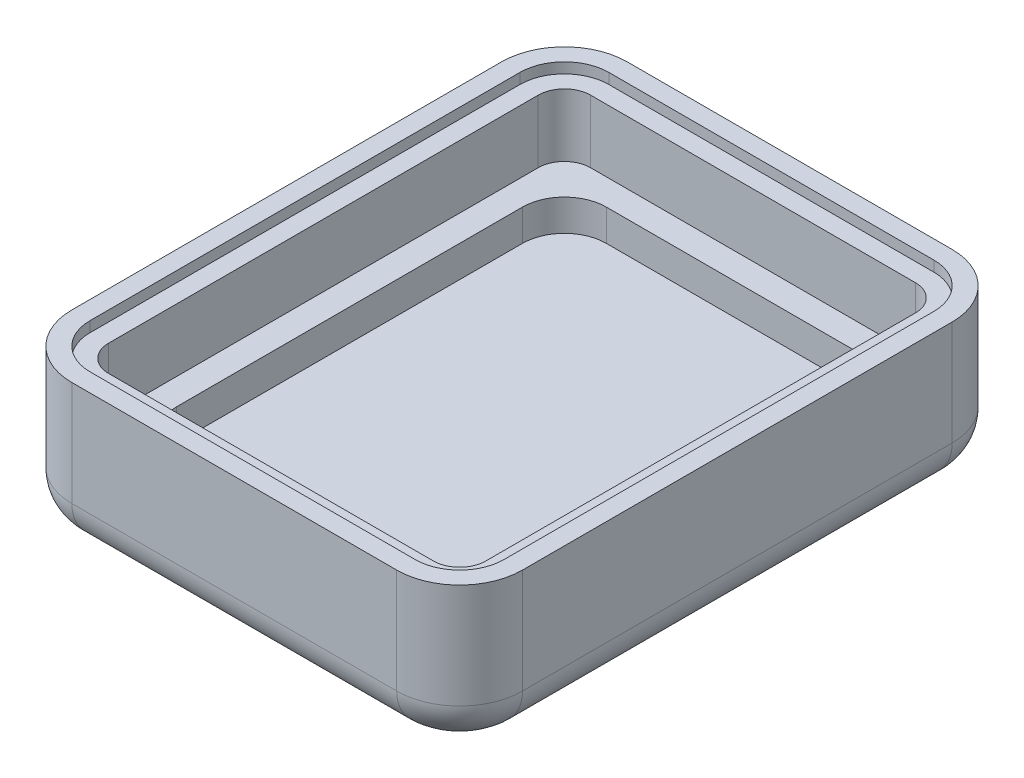
SolidWorks part; units mm, degrees
ref_plane "Front Plane" through (0, 0, 0) normal (0, 0, 1) x (1, 0, 0)
ref_plane "Top Plane" through (0, 0, 0) normal (0, 1, 0) x (1, 0, 0)
ref_plane "Right Plane" through (0, 0, 0) normal (1, 0, 0) x (0, 0, -1)
sketch "Sketch1" plane through (0, 0, 0) normal (0, 1, 0) x (1, 0, 0)
  line L1 (-7.75, -11.25) -> (7.75, -11.25) construction
  line L2 (-8.75, -10.25) -> (-8.75, 10.25) construction
  line L3 (-7.75, 11.25) -> (7.75, 11.25) construction
  line L4 (8.75, -10.25) -> (8.75, 10.25) construction
  line L5 (-8.75, -11.25) -> (8.75, 11.25) construction
  line L6 (-8.75, 11.25) -> (8.75, -11.25) construction
  line L7 (-7.75, -13.25) -> (7.75, -13.25)
  line L8 (-10.75, -10.25) -> (-10.75, 10.25)
  line L9 (-7.75, 13.25) -> (7.75, 13.25)
  line L10 (10.75, -10.25) -> (10.75, 10.25)
  line L11 (-10.75, -13.25) -> (10.75, 13.25) construction
  line L12 (-10.75, 13.25) -> (10.75, -13.25) construction
  arc A0 (-7.75, -11.25) -> (-8.75, -10.25) centre (-7.75, -10.25) cw construction
  arc A1 (7.75, -11.25) -> (8.75, -10.25) centre (7.75, -10.25) ccw construction
  arc A2 (7.75, 11.25) -> (8.75, 10.25) centre (7.75, 10.25) cw construction
  arc A3 (-8.75, 10.25) -> (-7.75, 11.25) centre (-7.75, 10.25) cw construction
  arc A4 (-10.75, 10.25) -> (-7.75, 13.25) centre (-7.75, 10.25) cw
  arc A5 (-7.75, -13.25) -> (-10.75, -10.25) centre (-7.75, -10.25) cw
  arc A6 (7.75, -13.25) -> (10.75, -10.25) centre (7.75, -10.25) ccw
  arc A7 (7.75, 13.25) -> (10.75, 10.25) centre (7.75, 10.25) cw
  point P0 (0, 0)
  point P18 (0, 0)
  dimension "D3" = 1
  dimension "D6" = 3
  dimension "D1" = 17.5
  dimension "D2" = 22.5
  dimension "D4" = 2
  dimension "D5" = 2
extrude "Boss-Extrude1" add sketch "Sketch1" along normal blind 2
sketch "Sketch2" plane through (0, 2, 0) normal (0, 1, 0) x (1, 0, 0)
  line L0 (7.75, 13.25) -> (-7.75, 13.25) construction
  line L1 (-7.75, -11.5) -> (7.75, -11.5)
  line L2 (-9, -10.25) -> (-9, 10.25)
  line L3 (-7.75, 11.5) -> (7.75, 11.5)
  line L4 (9, -10.25) -> (9, 10.25)
  line L5 (-9, -11.5) -> (9, 11.5) construction
  line L6 (-9, 11.5) -> (9, -11.5) construction
  line L7 (-7.75, -13.25) -> (7.75, -13.25)
  line L8 (-10.75, -10.25) -> (-10.75, 10.25)
  line L9 (-7.75, 13.25) -> (7.75, 13.25)
  line L10 (10.75, -10.25) -> (10.75, 10.25)
  line L11 (-10.75, -13.25) -> (10.75, 13.25) construction
  line L12 (-10.75, 13.25) -> (10.75, -13.25) construction
  line L13 (10.75, -10.25) -> (10.75, 10.25) construction
  arc A0 (-7.75, -11.5) -> (-9, -10.25) centre (-7.75, -10.25) cw
  arc A1 (7.75, -11.5) -> (9, -10.25) centre (7.75, -10.25) ccw
  arc A2 (7.75, 11.5) -> (9, 10.25) centre (7.75, 10.25) cw
  arc A3 (-9, 10.25) -> (-7.75, 11.5) centre (-7.75, 10.25) cw
  arc A4 (-7.75, -13.25) -> (-10.75, -10.25) centre (-7.75, -10.25) cw
  arc A5 (7.75, -13.25) -> (10.75, -10.25) centre (7.75, -10.25) ccw
  arc A6 (7.75, 13.25) -> (10.75, 10.25) centre (7.75, 10.25) cw
  arc A7 (-10.75, 10.25) -> (-7.75, 13.25) centre (-7.75, 10.25) cw
  point P0 (0, 0)
  point P18 (0, 0)
  dimension "D3" = 1.25
  dimension "D4" = 3
  dimension "D1" = 18
  dimension "D2" = 23
extrude "Boss-Extrude2" add sketch "Sketch2" along normal blind 5
sketch "Sketch3" plane through (0, 2, 0) normal (0, 1, 0) x (1, 0, 0)
  line L0 (9, -10.25) -> (-5.75, -10.25)
  line L1 (-7.75, -8.25) -> (-7.75, 8.25)
  line L2 (-5.75, 10.25) -> (9, 10.25)
  line L3 (9, 10.25) -> (9, 12.25)
  line L4 (9, 12.25) -> (-9.75, 12.25)
  line L5 (-9.75, 12.25) -> (-9.75, -12.25)
  line L6 (-9.75, -12.25) -> (9, -12.25)
  line L7 (9, -12.25) -> (9, -10.25)
  arc A0 (-5.75, -10.25) -> (-7.75, -8.25) centre (-5.75, -8.25) cw
  arc A1 (-7.75, 8.25) -> (-5.75, 10.25) centre (-5.75, 8.25) cw
  point P14 (-7.75, -10.25)
  dimension "D4" = 2
  dimension "D1" = 2
  dimension "D2" = 2
  dimension "D3" = 2
extrude "Boss-Extrude3" add sketch "Sketch3" along normal blind 1.5
fillet "Fillet1" radius 2 8 edges at (10.75, 0, 0) (9.8713, 0, 12.3713) (0, 0, 13.25) (-9.8713, 0, 12.3713) (-10.75, 0, 0) (-9.8713, 0, -12.3713) (0, 0, -13.25) (9.8713, 0, -12.3713)
sketch "Sketch4" plane through (0, 7, 0) normal (0, 1, 0) x (1, 0, 0)
  line L0 (7.75, 11.5) -> (-7.75, 11.5) construction
  line L3 (-7.75, 12.375) -> (7.75, 12.375)
  line L4 (9.875, 10.25) -> (9.875, -10.25)
  line L5 (7.75, -12.375) -> (-7.75, -12.375)
  line L6 (-9.875, -10.25) -> (-9.875, 10.25)
  line L7 (-10.75, 10.25) -> (-10.75, -10.25) construction
  line L8 (10.75, -10.25) -> (10.75, 10.25) construction
  line L9 (-7.75, -13.25) -> (7.75, -13.25) construction
  arc A1 (9.875, -10.25) -> (7.75, -12.375) centre (7.75, -10.25) cw
  arc A2 (-7.75, -12.375) -> (-9.875, -10.25) centre (-7.75, -10.25) cw
  arc A3 (-9.875, 10.25) -> (-7.75, 12.375) centre (-7.75, 10.25) cw
  arc A4 (7.75, 12.375) -> (9.875, 10.25) centre (7.75, 10.25) cw
  dimension "D5" = 2.125
  dimension "D1" = 0.875
  dimension "D2" = 0.875
  dimension "D3" = 0.875
  dimension "D4" = 0.875
extrude "Cut-Extrude1" cut sketch "Sketch4" against normal blind 0.5
